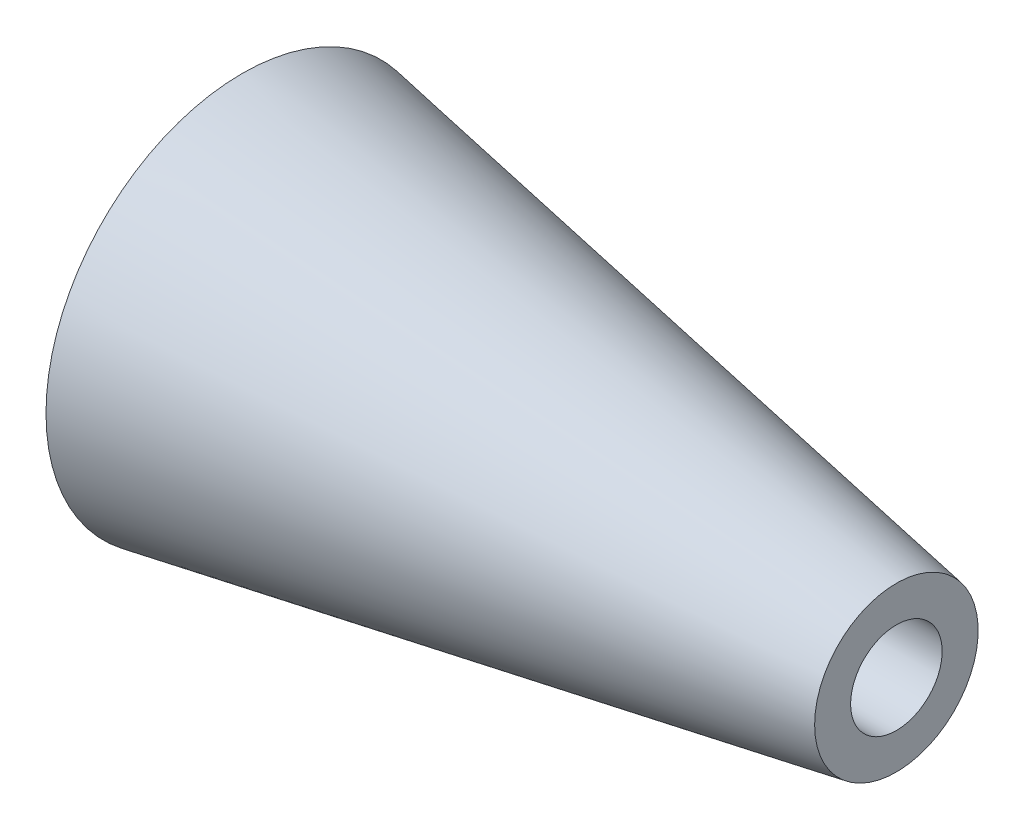
SolidWorks part; units mm, degrees
material "Nylon 101"
ref_plane "Front Plane" through (0, 0, 0) normal (0, 0, 1) x (1, 0, 0)
ref_plane "Top Plane" through (0, 0, 0) normal (0, 1, 0) x (1, 0, 0)
ref_plane "Right Plane" through (0, 0, 0) normal (1, 0, 0) x (0, 0, -1)
sketch "Sketch1" plane through (0, 0, 0) normal (0, 0, 1) x (1, 0, 0)
  line L0 (0, 0) -> (24.9011, 0) construction
  line L1 (0, 0.7) -> (10, 0.7)
  line L2 (10, 0.7) -> (10, 1.25)
  line L3 (10, 1.25) -> (0, 3)
  line L4 (0, 3) -> (0, 0.7)
  dimension "D1" = 0.7
  dimension "D2" = 10
  dimension "D3" = 1.25
  dimension "D4" = 3
revolve "Revolve1" add sketch "Sketch1" angle 360 about L0
sketch "Sketch2" plane through (10, 0, 0) normal (1, 0, 0) x (0, 0, -1)
  circle A0 centre (0, 0) radius 0.7
  circle A1 centre (0, 0) radius 0.5
  dimension "D1" = 1
extrude "Boss-Extrude1" [suppressed] add sketch "Sketch2" against normal blind 10
